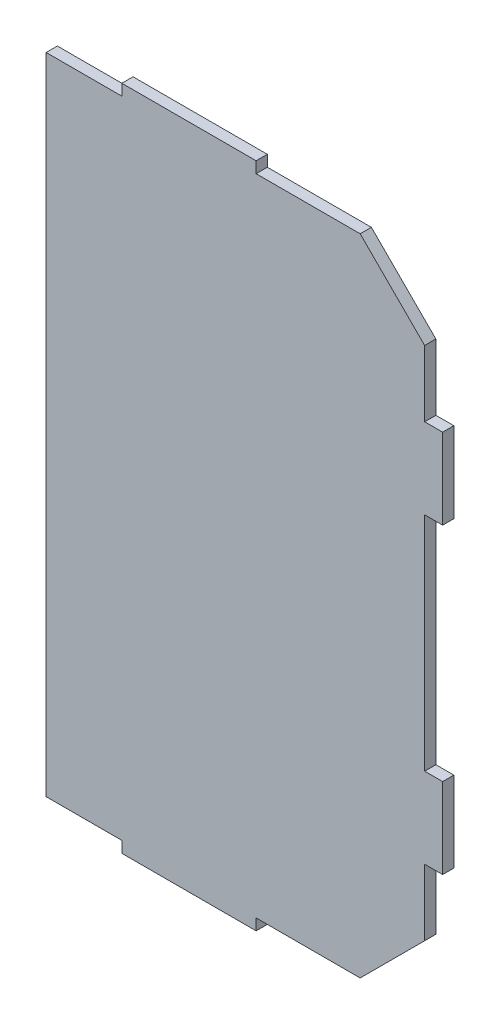
SolidWorks part; units mm, degrees
ref_plane "Front Plane" through (0, 0, 0) normal (0, 0, 1) x (1, 0, 0)
ref_plane "Top Plane" through (0, 0, 0) normal (0, 1, 0) x (1, 0, 0)
ref_plane "Right Plane" through (0, 0, 0) normal (1, 0, 0) x (0, 0, -1)
sketch "Sketch1" plane through (0, 0, 0) normal (0, 0, 1) x (1, 0, 0)
  line L13 (-398.8381, -315.4) -> (-271.8381, -315.4)
  line L14 (-398.8381, -315.4) -> (-398.8381, -304.8)
  line L16 (-271.8381, -315.4) -> (-271.8381, -304.8)
  line L18 (-398.8381, 304.8) -> (-398.8381, 315.4)
  line L19 (-398.8381, 315.4) -> (-271.8381, 315.4)
  line L20 (-271.8381, 304.8) -> (-271.8381, 315.4)
  line L22 (-64.0957, 181.2953) -> (-74.217, 181.2953) construction
  line L23 (-95.4317, 181.2953) -> (-112.4317, 181.2953)
  line L24 (-64.0957, -181.1047) -> (-74.217, -181.1047) construction
  line L25 (-64.0957, -104.9047) -> (-74.217, -104.9047) construction
  line L31 (-112.4317, 243.8009) -> (-112.4317, 181.2953)
  line L34 (-398.8381, 476) -> (-398.8381, -476) construction
  line L35 (-271.8381, 476) -> (-271.8381, -476) construction
  line L37 (-398.8381, 304.8) -> (-470.4317, 304.8)
  line L39 (-173.4308, 304.8) -> (-271.8381, 304.8)
  line L41 (-112.4317, 243.8009) -> (-112.4317, -243.8009) construction
  line L42 (-112.4317, -243.8009) -> (-112.4317, -589.3418) construction
  line L43 (-173.4308, 304.8) -> (-112.4317, 243.8009)
  line L44 (-470.4317, -304.8) -> (-398.8381, -304.8)
  line L45 (-271.8381, 315.4953) -> (-271.8381, 304.8953) construction
  line L46 (-173.4308, -304.8) -> (-112.4317, -243.8009)
  line L47 (-64.0957, 105.0953) -> (-74.217, 105.0953) construction
  line L48 (-95.4317, 105.0953) -> (-112.4317, 105.0953)
  line L49 (-95.4317, -181.1047) -> (-112.4317, -181.1047)
  line L50 (-95.4317, -104.9047) -> (-112.4317, -104.9047)
  line L51 (-95.4317, 192.9083) -> (-95.4317, -192.6066) construction
  line L53 (-95.4317, 181.2953) -> (-95.4317, 105.0953)
  line L54 (-95.4317, -104.9047) -> (-95.4317, -181.1047)
  line L55 (-112.4317, -181.1047) -> (-112.4317, -243.8009)
  line L56 (-112.4317, 105.0953) -> (-112.4317, -104.9047)
  line L57 (-173.4308, -304.8) -> (-271.8381, -304.8)
  line L58 (-398.8381, 315.4953) -> (-398.8381, 304.8953) construction
  line L59 (-470.4317, 304.8) -> (-470.4317, -304.8)
  dimension "D2" = 135
  dimension "D3" = 98.4073
  dimension "D4" = 135
  dimension "D5" = 17
  dimension "D6" = 358
  dimension "D9" = 476
  dimension "D13" = 476
other "AlignGroup1"
extrude "Boss-Extrude1" add sketch "Sketch1" along normal blind 10.6
